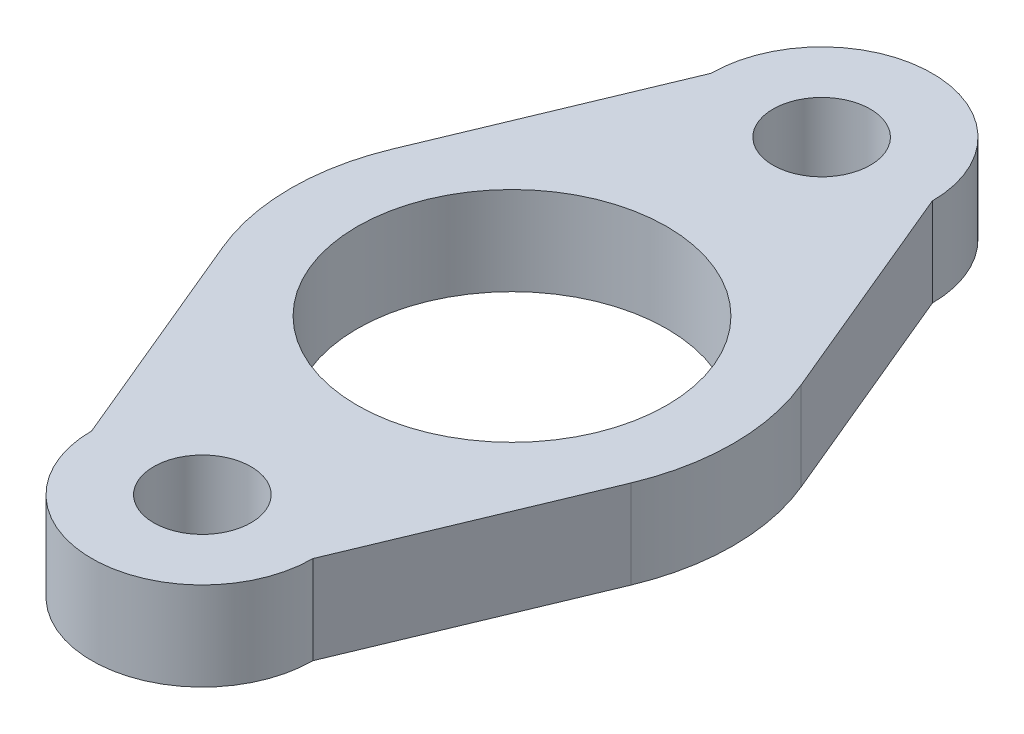
SolidWorks part; units mm, degrees
ref_plane "Front Plane" through (0, 0, 0) normal (0, 0, 1) x (1, 0, 0)
ref_plane "Top Plane" through (0, 0, 0) normal (0, 1, 0) x (1, 0, 0)
ref_plane "Right Plane" through (0, 0, 0) normal (1, 0, 0) x (0, 0, -1)
sketch "Sketch2" plane through (0, 0, 0) normal (0, 1, 0) x (1, 0, 0)
  line L0 (-30.4992, 0) -> (39.6772, 0) construction
  line L1 (0, -35) -> (0, 51.6086) construction
  line L2 (-12.5, 35) -> (-23.0769, 9.6154)
  line L3 (12.5, 35) -> (23.0769, 9.6154)
  line L4 (-12.5, -35) -> (-23.0769, -9.6154)
  line L5 (12.5, -35) -> (23.0769, -9.6154)
  line L6 (-20, -17) -> (-20, -95)
  line L7 (-25, -95) -> (25, -95)
  line L8 (20, -95) -> (20, -17)
  line L10 (25, -95) -> (25, -105)
  line L11 (25, -105) -> (-25, -105)
  line L12 (-25, -105) -> (-25, -95)
  arc A0 (23.0769, -9.6154) -> (23.0769, 9.6154) centre (0, 0) ccw
  circle A1 centre (0, 0) radius 17.5
  circle A2 centre (0, 35) radius 5.5
  circle A3 centre (0, 35) radius 10 construction
  circle A4 centre (0, -35) radius 5.5
  circle A5 centre (0, -35) radius 10 construction
  arc A6 (12.5, 35) -> (-12.5, 35) centre (0, 35) ccw
  arc A7 (-12.5, -35) -> (12.5, -35) centre (0, -35) ccw
  arc A8 (-23.0769, 9.6154) -> (-23.0769, -9.6154) centre (0, 0) ccw
  circle A9 centre (0, 0) radius 20
  point P13 (0, 47.5)
  point P14 (0, -47.5)
  dimension "D1" = 25
  dimension "D2" = 25
  dimension "D4" = 50
  dimension "D6" = 35
  dimension "D7" = 40
  dimension "D9" = 105
  dimension "D10" = 20
  dimension "D11" = 11
  dimension "D3" = 70
  dimension "D5" = 35
  dimension "D8" = 95
  dimension "D12" = 50
  dimension "D13" = 5
  dimension "D14" = 5
  dimension "D15" = 10
  dimension "10" = 10
  dimension "D16" = 78
  dimension "D17" = 78
extrude "Boss-Extrude3" add sketch "Sketch2" along normal blind 10 contours L2 A8 L4 A7 L5 A0 L3 A6 A9 A2 A4 | A9 A1
